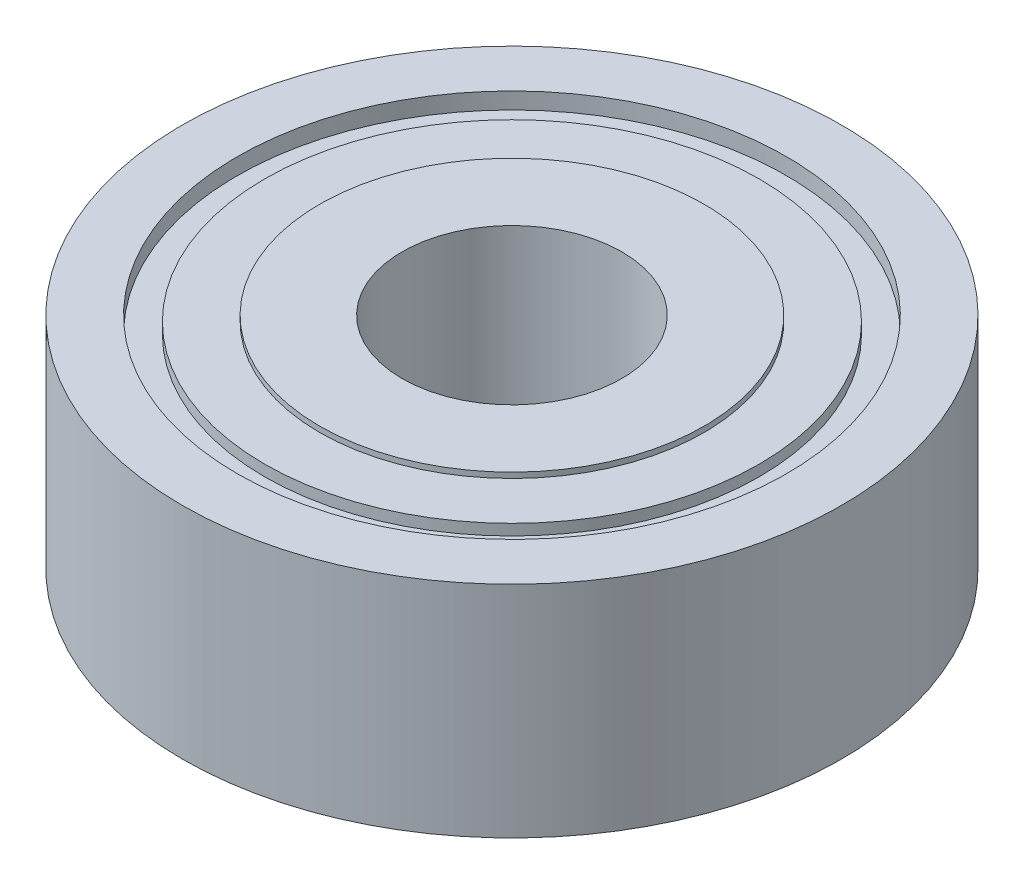
SolidWorks part; units mm, degrees
ref_plane "Front Plane" through (0, 0, 0) normal (0, 0, 1) x (1, 0, 0)
ref_plane "Top Plane" through (0, 0, 0) normal (0, 1, 0) x (1, 0, 0)
ref_plane "Right Plane" through (0, 0, 0) normal (1, 0, 0) x (0, 0, -1)
sketch "Sketch1" plane through (0, 0, 0) normal (0, 1, 0) x (1, 0, 0)
  circle A0 centre (0, 0) radius 4
  circle A1 centre (0, 0) radius 7
  dimension "D1" = 8
  dimension "D2" = 14
extrude "Boss-Extrude1" add sketch "Sketch1" along normal mid plane 8
sketch "Sketch3" plane through (0, 0, 0) normal (0, 1, 0) x (1, 0, 0)
  circle A0 centre (0, 0) radius 7
  circle A1 centre (0, 0) radius 9
  dimension "D1" = 18
  dimension "D2" = 14
extrude "Boss-Extrude2" add sketch "Sketch3" along normal mid plane 7.6
sketch "Sketch4" plane through (0, 0, 0) normal (0, 1, 0) x (1, 0, 0)
  circle A0 centre (0, 0) radius 9
  circle A1 centre (0, 0) radius 1
  circle A2 centre (0, 0) radius 10
  dimension "D1" = 18
  dimension "D2" = 20
extrude "Boss-Extrude3" add sketch "Sketch4" along normal mid plane 6.8 contours A2 A0
sketch "Sketch5" plane through (0, 0, 0) normal (0, 1, 0) x (1, 0, 0)
  circle A0 centre (0, 0) radius 10
  circle A1 centre (0, 0) radius 12
  dimension "D1" = 20
  dimension "D2" = 24
extrude "Boss-Extrude4" add sketch "Sketch5" along normal mid plane 8
